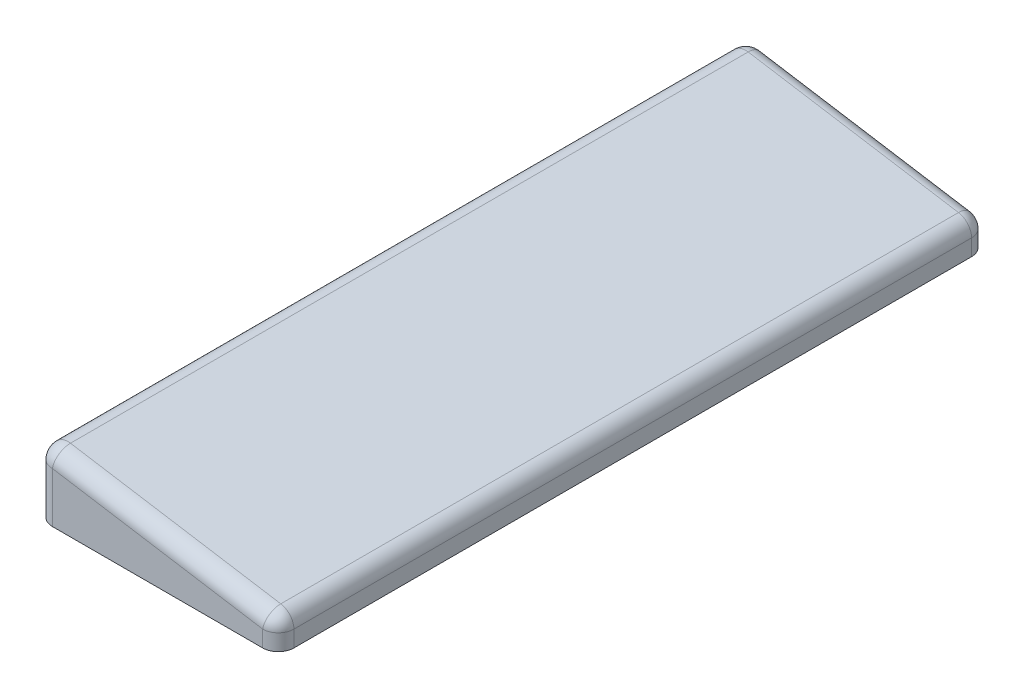
SolidWorks part; units mm, degrees
ref_plane "Front Plane" through (0, 0, 0) normal (0, 0, 1) x (1, 0, 0)
ref_plane "Top Plane" through (0, 0, 0) normal (0, 1, 0) x (1, 0, 0)
ref_plane "Right Plane" through (0, 0, 0) normal (1, 0, 0) x (0, 0, -1)
sketch "Sketch1" plane through (0, 0, 0) normal (0, 0, 1) x (1, 0, 0)
  line L0 (0, 0) -> (155, 0)
  line L1 (0, 0) -> (0, 44)
  line L2 (0, 44) -> (155, 19)
  line L3 (155, 19) -> (155, 0)
  dimension "D1" = 155
  dimension "D2" = 0
  dimension "D3" = 44
  dimension "D4" = 19
extrude "Boss-Extrude1" add sketch "Sketch1" against normal blind 455
fillet "Fillet1" radius 10 1 edges at (155, 19, -227.5)
fillet "Fillet2" radius 10 1 edges at (0, 44, -227.5)
fillet "Fillet3" radius 10 5 edges at (155, 5.2418, 0) (152.6133, 16.9674, 0) (0, 16.1289, 0) (3.5163, 39.8711, 0) (79.0923, 31.2432, 0)
fillet "Fillet4" radius 10 5 edges at (155, 5.2418, -455) (152.6133, 16.9674, -455) (0, 16.1289, -455) (3.5163, 39.8711, -455) (79.0923, 31.2432, -455)
